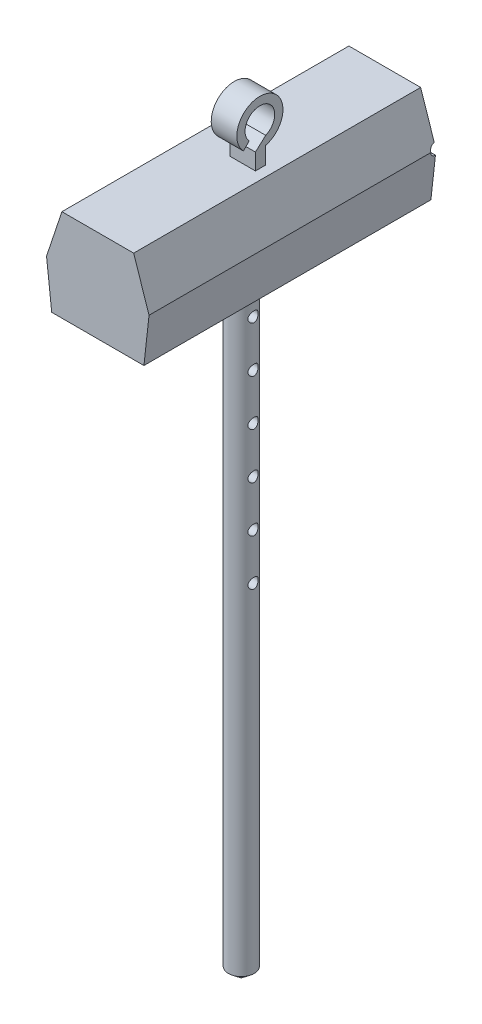
SolidWorks part; units mm, degrees
ref_plane "Front Plane" through (0, 0, 0) normal (0, 0, 1) x (1, 0, 0)
ref_plane "Top Plane" through (0, 0, 0) normal (0, 1, 0) x (1, 0, 0)
ref_plane "Right Plane" through (0, 0, 0) normal (1, 0, 0) x (0, 0, -1)
sketch "Sketch1" plane through (0, 0, 0) normal (0, 0, 1) x (1, 0, 0)
  line L0 (-646.673, 0) -> (0, 0) construction
  line L1 (0, -646.673) -> (0, 31686.9757) construction
  line L2 (-35, 45) -> (35, 45)
  line L3 (0, 45) -> (0, -45) construction
  line L4 (-45, -45) -> (45, -45)
  line L5 (-45, -45) -> (-50, 0)
  line L6 (35, 45) -> (50, 0)
  line L7 (45, -45) -> (50, 0)
  line L8 (50, 0) -> (31686.9757, 0) construction
  line L9 (-35, 45) -> (-50, 0)
  dimension "D1" = 35
  dimension "D2" = 45
  dimension "D3" = 45
  dimension "D4" = 90
  dimension "D5" = 50
extrude "Boss-Extrude1" add sketch "Sketch1" along normal blind 280
sketch "Sketch2" plane through (0, 45, 0) normal (0, 1, 0) x (1, 0, 0)
  line L0 (0, 0) -> (0, -280) construction
  line L1 (35, 0) -> (-35, 0) construction
  line L2 (35, -280) -> (-35, -280) construction
  dimension "D1" = 280
sketch "Sketch3" plane through (0, 0, 0) normal (1, 0, 0) x (0, 0, -1)
  line L0 (-146.8457, 48.8591) -> (-146.8457, -67.8508) construction
  line L1 (-91.373, 139.7088) -> (-174.7926, 55.8301) construction
  line L2 (-141.1883, 70.1219) -> (-141.1883, 45)
  line L3 (0, 45) -> (-280, 45) construction
  line L4 (-151.1834, 60.9726) -> (-151.1834, 45)
  line L5 (-146.8457, 45) -> (-141.1883, 45)
  line L6 (-157.2971, 73.4219) -> (-162.9394, 67.7486)
  line L7 (-151.1834, 45) -> (-151.1834, 60.9726)
  line L8 (-151.1834, 45) -> (-146.8457, 45)
  line L9 (-146.8457, 60.9726) -> (-151.1834, 60.9726)
  line L10 (-141.1883, 70.1219) -> (-151.1834, 60.9726)
  arc A0 (-146.8457, 60.9726) -> (-162.9394, 67.7486) centre (-146.8457, 83.4726) ccw
  arc A2 (-141.1883, 70.1219) -> (-157.2971, 73.4219) centre (-146.8457, 83.4726) ccw
  dimension "D1" = 45
extrude "Boss-Extrude3" add sketch "Sketch3" along normal blind 25 contours A2 L2 A0 L6 | L9 A0 L2 L10 | A0 L9 L4 L8 L5 L2
sketch "Sketch4" plane through (0, -45, 0) normal (0, -1, 0) x (1, 0, 0)
  line L0 (0, 0) -> (0, 280) construction
  line L1 (-45, 0) -> (45, 0) construction
  line L2 (-45, 280) -> (45, 280) construction
  circle A0 centre (0, 140) radius 12.5
  dimension "D1" = 25
extrude "Boss-Extrude4" add sketch "Sketch4" along normal blind 600
sketch "Sketch5" plane through (0, 0, 0) normal (1, 0, 0) x (0, 0, -1)
  line L0 (-152.5, -645) -> (-127.5, -645)
  line L4 (-140, -618.4792) -> (-140, 71.5208) construction
  line L6 (-140, -645) -> (-140, -655)
  line L7 (-127.5, -645) -> (-140, -655)
  line L8 (-140, -645) -> (-127.5, -645)
  dimension "D1" = 10
revolve "Revolve1" add sketch "Sketch5" angle 360 about L4
sketch "Sketch6" plane through (0, 0, 0) normal (1, 0, 0) x (0, 0, -1)
  line L0 (-140, 45) -> (-140, -655) construction
  line L1 (0, 45) -> (-280, 45) construction
  line L2 (-280, -45) -> (0, -45) construction
  circle A0 centre (-140, -90) radius 5
  circle A1 centre (-140, -135) radius 5
  circle A2 centre (0, 0) radius 5
  circle A3 centre (-140, -225) radius 5
  circle A4 centre (-140, -270) radius 5
  circle A5 centre (-140, -315) radius 5
  circle A7 centre (-140, -180) radius 5
  point P3 (-140, 45)
  dimension "D2" = 10
  dimension "D3" = 45
  dimension "D4" = 10
  dimension "D7" = 10
  dimension "D6" = 10
  dimension "D11" = 10
  dimension "D1" = 45
  dimension "D5" = 45
  dimension "D8" = 45
  dimension "D9" = 45
  dimension "D10" = 45
extrude "Cut-Extrude1" cut sketch "Sketch6" against normal through all and the other way through all
